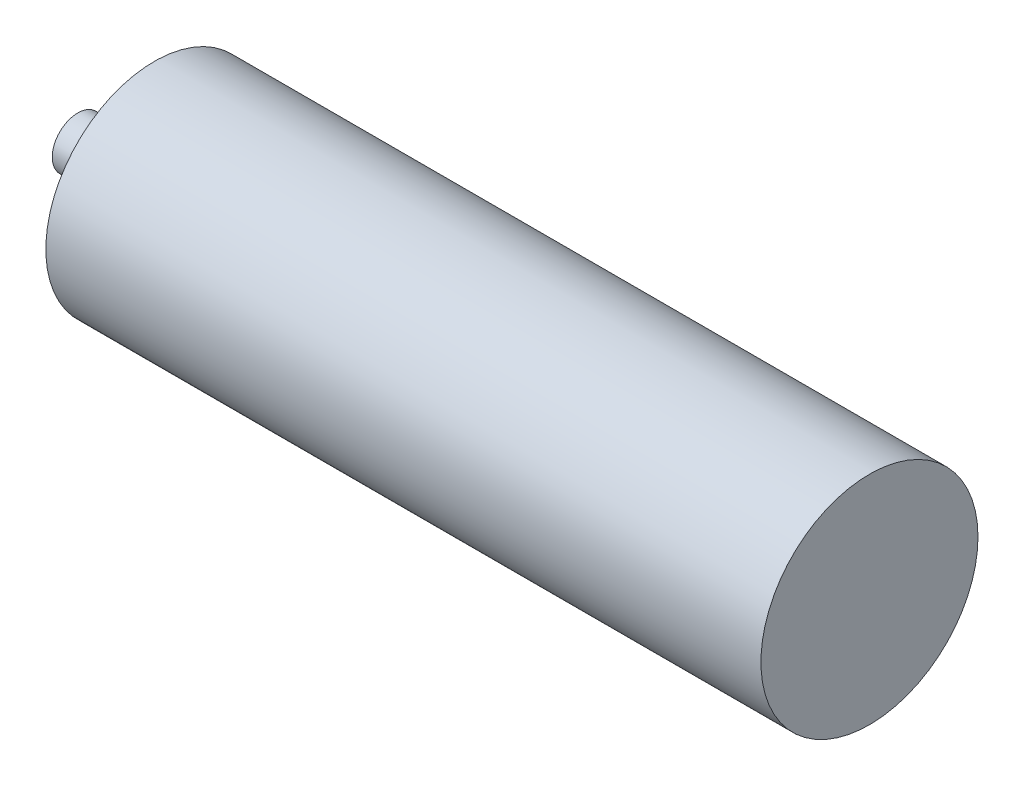
SolidWorks part; units mm, degrees
ref_plane "Front Plane" through (0, 0, 0) normal (1, 0, 0) x (0, 1, 0)
ref_plane "Top Plane" through (0, 0, 0) normal (0, 0, 1) x (0, 1, 0)
ref_plane "Right Plane" through (0, 0, 0) normal (0, 1, 0) x (-1, 0, 0)
sketch "Sketch1" plane through (0, 0, 0) normal (1, 0, 0) x (0, 1, 0)
  circle A0 centre (-10.2713, 8.8744) radius 26.9875
  dimension "D1" = 53.975
extrude "Boss-Extrude1" add sketch "Sketch1" along normal blind 177.8
sketch "Sketch4" plane through (0, 0, 0) normal (-1, 0, 0) x (0, 0, 1)
  circle A0 centre (8.8744, -10.2713) radius 6.35
  circle A1 centre (8.8744, -10.2713) radius 26.9875 construction
  dimension "D1" = 0
  dimension "D2" = 12.7
extrude "Boss-Extrude3" add sketch "Sketch4" along normal blind 19.05
sketch "Sketch5" plane through (-19.05, 0, 0) normal (-1, 0, 0) x (0, 0, 1)
  circle A0 centre (8.8744, -10.2713) radius 4.2286
  circle A1 centre (8.8744, -10.2713) radius 6.35 construction
  dimension "D1" = 0
